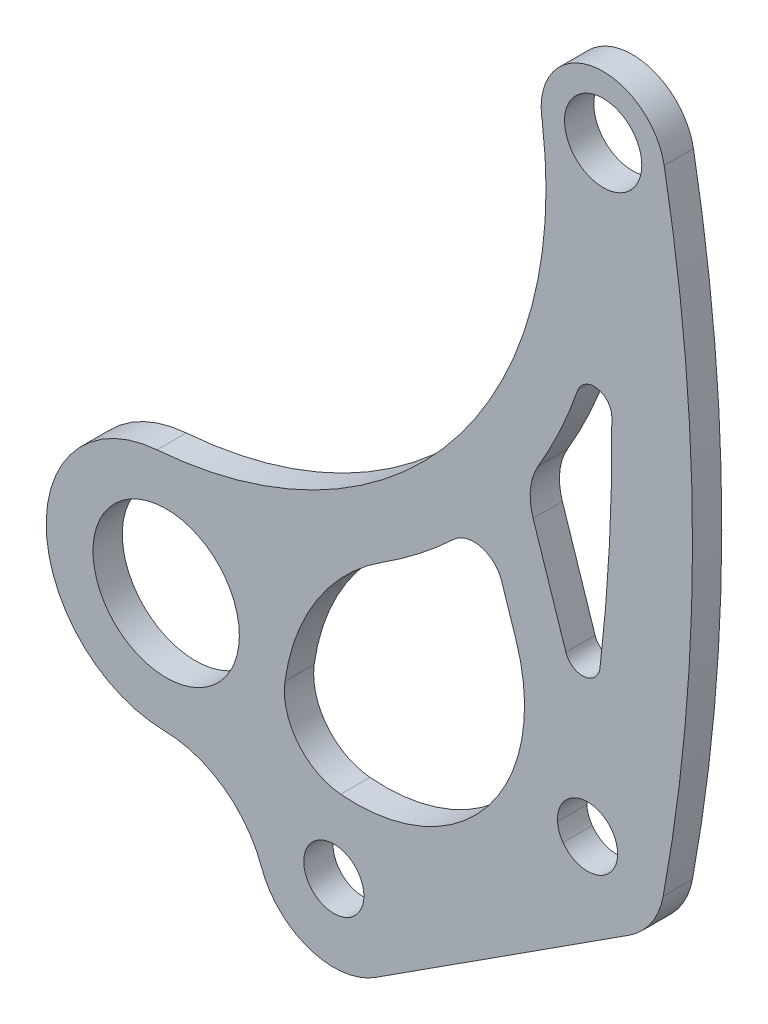
SolidWorks part; units mm, degrees
material "6061-T6 (SS)"
ref_plane "Front Plane" through (0, 0, 0) normal (0, 0, 1) x (1, 0, 0)
ref_plane "Top Plane" through (0, 0, 0) normal (0, 1, 0) x (1, 0, 0)
ref_plane "Right Plane" through (0, 0, 0) normal (1, 0, 0) x (0, 0, -1)
sketch "Sketch2" plane through (0, 0, 0) normal (0, 0, 1) x (1, 0, 0)
  line L0 (0, 0) -> (45.72, 0) construction
  line L1 (45.72, 0) -> (47.4133, 66.0183) construction
  line L2 (47.4133, 66.0183) -> (0, 0) construction
  line L3 (-9.9543, 8.3886) -> (42.2663, 70.3558)
  line L4 (54.1443, 66.0101) -> (54.0639, -0.0102)
  line L5 (46.5729, -8.3002) -> (1.3307, -12.9493)
  line L6 (-6.2268, 4.9225) -> (44.1256, 68.6173)
  line L7 (0.8114, -7.8959) -> (46.0536, -3.2468)
  line L8 (48.9813, -0.1295) -> (51.601, 65.852)
  line L9 (0, 0) -> (18.1918, -17.7262) construction
  line L10 (45.72, 0) -> (38.8832, 9.7026) construction
  line L11 (45.72, 0) -> (42.0108, 11.275) construction
  line L12 (45.72, 0) -> (44.9726, 11.8459) construction
  line L13 (47.2407, 59.2895) -> (45.9339, 8.3412)
  line L14 (45.72, 0) -> (36.8585, 26.9366) construction
  line L15 (34.7499, 24.3546) -> (40.5957, 6.585)
  line L16 (38.8824, 29.7758) -> (45.9339, 8.3412)
  line L17 (41.2892, 13.4683) -> (38.6201, 12.5902) construction
  line L18 (41.2892, 13.4683) -> (43.9584, 14.3464) construction
  line L19 (0, 0) -> (18.1918, -17.7262) construction
  line L20 (-7.2141, -10.8357) -> (13.5678, -24.6716)
  line L21 (50.2373, -7.0153) -> (22.7092, -24.7415)
  line L22 (10.645, 7.4925) -> (25.015, -12.9236)
  line L23 (41.2027, 7.0153) -> (13.6745, -10.7109)
  line L26 (237.1837, -665.5499) -> (-723.8072, 270.8428) construction
  circle A0 centre (0, 0) radius 7.9375
  circle A1 centre (45.72, 0) radius 3.2639
  circle A2 centre (47.4133, 66.0183) radius 4.191
  circle A3 centre (0, 0) radius 13.0175
  circle A4 centre (45.72, 0) radius 8.3439
  circle A5 centre (47.4133, 66.0183) radius 6.731
  circle A8 centre (-4.5053, 58.5645) radius 45.72
  circle A9 centre (-4.5053, 58.5645) radius 52.07
  circle A10 centre (-133.3933, 33.155) radius 190.5
  circle A11 centre (-142.1385, 38.656) radius 190.5
  circle A13 centre (18.1918, -17.7262) radius 3.2639
  circle A14 centre (18.1918, -17.7262) radius 8.3439
  point P29 (47.2407, 59.2895)
  point P30 (45.72, 0)
  dimension "D1" = 8.382
  dimension "D2" = 6.5278
  dimension "D3" = 15.875
  dimension "D13" = 381
  dimension "D14" = 381
  dimension "D17" = 91.44
  dimension "D19" = 6.5278
  dimension "2.7" = 45.72
  dimension "D5" = 66.04
  dimension "D6" = 5.08
  dimension "D7" = 2.54
  dimension "D8" = 5.08
  dimension "D9" = 81.28
  dimension "D4" = 54.83
  dimension "D10" = 71.79
  dimension "D11" = 86.39
  dimension "D12" = 6.35
  dimension "D15" = 25.4
  dimension "D18" = 5.08
extrude "Boss-Extrude1" add sketch "Sketch2" along normal blind 3.175 contours A4 L23 L15 | A9 A2 L8 A5 | A9 A5 L8 A2 | A11 A5 A9 A2 | A5 A11 A2 L6 | A2 A11 A5 L6 | A11 A2 A9 A5 | A11 A4 L8 A5 A9 | A5 L8 A4 L4 | A4 A10 A5 L4 | A11 A4 L8 A1 L7 | A11 A1 L8 A4 | L7 A11 A1 A4 | A4 A11 L7 | A11 L7 A1 | A14 L21 A11 L5 L22 | A14 L5 A13 | L5 A14 | A14 L5 L22 L23 | A14 L22 L5 | L5 A11 A4 L7 L23 L22 | A11 L5 A4 | A11 L21 A4 L5 | A14 L5 A3 L20 | A14 L23 L22 L7 A3 L5 | A9 A3 L7 A0 L6 | A3 A9 L6 | L6 A9 A0 A3 | A9 L6 A0 | A9 A0 L7 A3 | A4 L15 L23 L7 | A9 L15 L23 A4 L16 | A3 A9 L13 A5 L6 A8 | A11 A9 A5 | A9 A11 L13 | L23 L7 L22 | A8 A3 L6
ref_plane "Plane2" through (45.72, 0, 0) normal (-0.576, 0.8174, 0) x (0.8174, 0.576, 0)
split line "Split Line2"
ref_plane "Plane3" through (45.72, 0, 0) normal (-0.063, 0.998, 0) x (0.998, 0.063, 0)
split line "Split Line3"
fillet "Fillet1" [suppressed] radius 2.54
fillet "Fillet2" [suppressed] radius 3.81
fillet "Fillet3" radius 1.905 2 edges at (45.9339, 8.3412, 1.5875) (47.5238, 56.5014, 1.5875)
fillet "Fillet4" radius 6.35 1 edges at (38.8824, 29.7758, 1.5875)
sketch "Sketch3" plane through (0, 0, 3.175) normal (0, 0, 1) x (1, 0, 0)
  line L0 (0, 0) -> (18.1918, -17.7262) construction
  line L1 (34.7499, 24.3546) -> (40.585, 6.6176) construction
  line L2 (18.1918, -17.7262) -> (45.72, 0) construction
  circle A0 centre (45.72, 0) radius 8.3439
  circle A1 centre (18.1918, -17.7262) radius 8.3439
  circle A2 centre (0, 0) radius 13.0175
  circle A3 centre (0, 0) radius 7.9375 construction
  circle A4 centre (18.1918, -17.7262) radius 3.2639 construction
  arc A5 (48.3881, 1.88) -> (42.4626, -0.2055) centre (45.72, 0) ccw construction
  circle A7 centre (20.5527, 8.8458) radius 18.3327
  circle A9 centre (19.523, -2.744) radius 6.6973
  circle A11 centre (36.0489, -5.0667) radius 23.3857
  arc A12 (9.8489, 8.5121) -> (34.7499, 24.3546) centre (-4.5053, 58.5645) ccw construction
  line M20 (21.3187, -5.7886) -> (11.0749, -6.8412)
  arc M21 (11.0749, -6.8412) -> (9.8489, 8.5121) centre (0, 0) ccw
  arc M22 (9.8489, 8.5121) -> (34.7499, 24.3546) centre (-4.5053, 58.5645) ccw
  line M23 (34.7499, 24.3546) -> (40.585, 6.6176)
  line M24 (40.585, 6.6176) -> (21.3187, -5.7886)
  dimension "D1" = 5.08
  dimension "D2" = 5.08
  dimension "D3" = 5.08
extrude "Boss-Extrude2" add sketch "Sketch3" against normal blind 3.175 contours A7 M24 M23 | A9 M21 M20 | A9 A11 M20 | A11 A2 M22
sketch "Sketch4" plane through (0, 0, 0) normal (0, 0, 1) x (1, 0, 0)
  line L0 (0, 0) -> (18.1918, -17.7262) construction
  line L1 (34.7499, 24.3546) -> (37.9672, 14.5748) construction
  line L2 (18.1918, -17.7262) -> (45.72, 0) construction
  line L3 (12.8908, -1.8118) -> (38.5393, 5.3003)
  line L4 (38.5393, 5.3003) -> (21.3187, -5.7886) construction
  circle A0 centre (45.72, 0) radius 8.3439
  circle A1 centre (18.1918, -17.7262) radius 8.3439
  circle A2 centre (0, 0) radius 13.0175
  circle A7 centre (20.5527, 8.8458) radius 18.3327
  circle A9 centre (19.523, -2.744) radius 6.6973
  circle A10 centre (0, 0) radius 7.9375 construction
  circle A11 centre (18.1918, -17.7262) radius 3.2639 construction
  arc A12 (48.3881, 1.88) -> (42.4626, -0.2055) centre (45.72, 0) ccw construction
  dimension "D1" = 5.08
  dimension "D2" = 5.08
  dimension "D3" = 5.08
extrude "Cut-Extrude1" cut sketch "Sketch4" along normal blind 12.065 contours A9 A7 L3 | L3 A9
fillet "Fillet5" radius 3.175 1 edges at (34.7499, 24.3546, 1.5875)
sketch "Sketch5" plane through (0, 0, 3.175) normal (0, 0, 1) x (1, 0, 0)
  line L0 (0, 0) -> (18.1918, -17.7262) construction
  line L1 (-7.2141, -10.8357) -> (-15.113, -22.7002)
  line L2 (-31.7354, 22.057) -> (17.3802, -25.8014) construction
  line L3 (-15.113, -22.7002) -> (13.5678, -34.65)
  line L4 (13.5678, -34.65) -> (13.5678, -24.6716)
  line L5 (-7.2141, -10.8357) -> (13.5678, -24.6716) construction
  circle A1 centre (18.1918, -17.7262) radius 3.2639 construction
  arc A2 (10.3391, -20.5466) -> (-0.1969, -13.016) centre (-0.3691, -24.3926) ccw
  arc A3 (10.3391, -20.5466) -> (13.5678, -24.6716) centre (18.1918, -17.7262) ccw
  arc A4 (-7.2141, -10.8357) -> (-0.1969, -13.016) centre (0, 0) ccw
  arc A5 (-0.9985, 12.9792) -> (-7.2141, -10.8357) centre (0, 0) ccw construction
  arc A6 (13.5678, -24.6716) -> (22.7092, -24.7415) centre (18.1918, -17.7262) ccw construction
  point P15 (0, 0)
  point P25 (0, 0)
  point P26 (0, 0)
  dimension "D1" = 6.35
extrude "Cut-Extrude2" cut sketch "Sketch5" against normal through all
equation "\"Droop angle\"= 54.83"
equation "\"Static angle\"= 71.79"
equation "\"Jounce angle\"= 86.39"
equation "\"D4@Sketch2\"=\"Droop angle\""
equation "\"D10@Sketch2\"=\"Static angle\""
equation "\"D11@Sketch2\"=\"Jounce angle\""
equation "\"DL Rocker Angle\"= 50.124deg"
equation "\"DL Rocker Length\"= 1.0in"
equation "\"D15@Sketch2\"=\"DL Rocker Length\""
